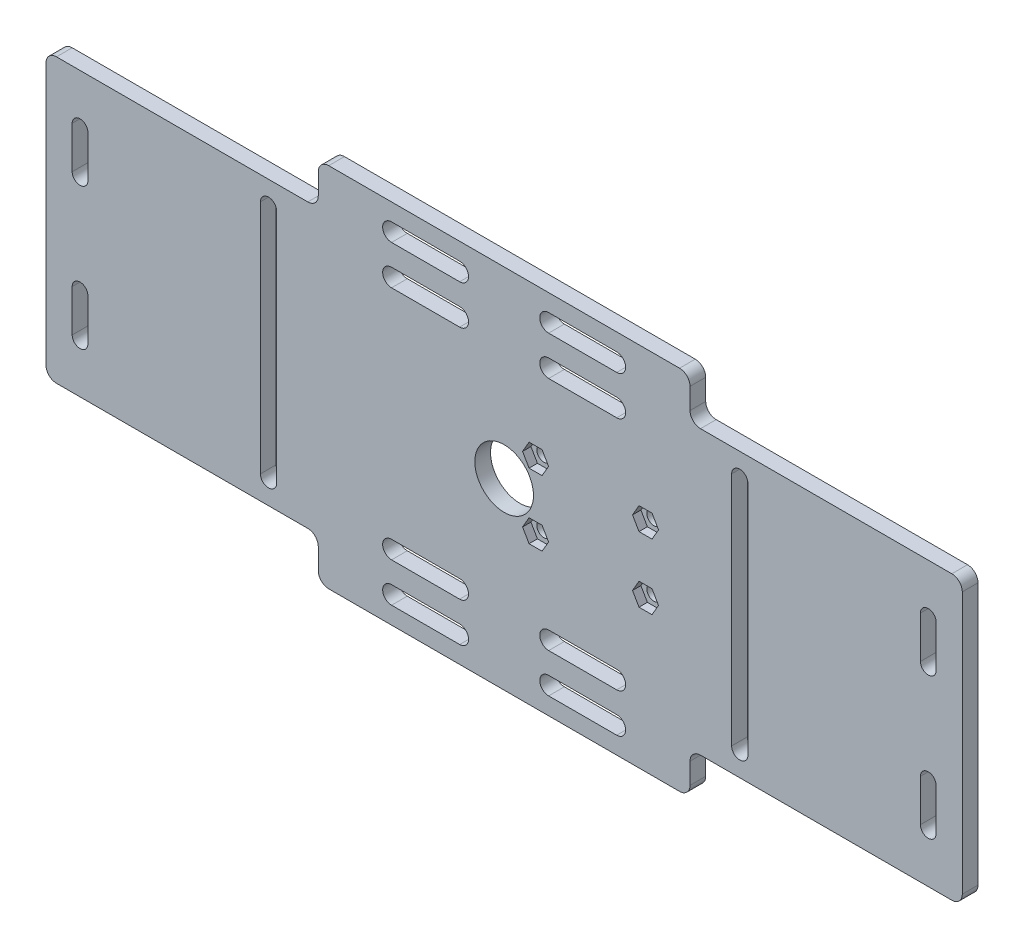
SolidWorks part; units mm, degrees
ref_plane "前基準面" through (0, 0, 0) normal (0, 0, 1) x (1, 0, 0)
ref_plane "上基準面" through (0, 0, 0) normal (0, 1, 0) x (1, 0, 0)
ref_plane "右基準面" through (0, 0, 0) normal (1, 0, 0) x (0, 0, -1)
sketch "草圖1" plane through (0, 0, 0) normal (0, 0, 1) x (1, 0, 0)
  line L0 (35.5, 33) -> (35.5, 29)
  line L1 (-33.5, 35) -> (33.5, 35)
  line L2 (-87.5, 25) -> (-87.5, -25)
  line L3 (-33.5, -35) -> (33.5, -35)
  line L4 (87.5, 25) -> (87.5, -25)
  line L5 (-87.5, 35) -> (87.5, -35) construction
  line L6 (-87.5, -35) -> (87.5, 35) construction
  line L7 (37.5, 27) -> (85.5, 27)
  line L8 (0, 71.4811) -> (0, -70.0061) construction
  line L9 (-113.0104, 0) -> (128.372, 0) construction
  line L10 (-37.5, 27) -> (-85.5, 27)
  line L11 (-35.5, 33) -> (-35.5, 29)
  line L12 (37.5, -27) -> (85.5, -27)
  line L13 (35.5, -33) -> (35.5, -29)
  line L14 (-35.5, -33) -> (-35.5, -29)
  line L15 (-37.5, -27) -> (-85.5, -27)
  arc A0 (35.5, 33) -> (33.5, 35) centre (33.5, 33) ccw
  arc A1 (37.5, 27) -> (35.5, 29) centre (37.5, 29) cw
  arc A2 (87.5, 25) -> (85.5, 27) centre (85.5, 25) ccw
  arc A3 (-87.5, 25) -> (-85.5, 27) centre (-85.5, 25) cw
  arc A4 (-37.5, 27) -> (-35.5, 29) centre (-37.5, 29) ccw
  arc A5 (-35.5, 33) -> (-33.5, 35) centre (-33.5, 33) cw
  arc A6 (87.5, -25) -> (85.5, -27) centre (85.5, -25) cw
  arc A7 (37.5, -27) -> (35.5, -29) centre (37.5, -29) ccw
  arc A8 (35.5, -33) -> (33.5, -35) centre (33.5, -33) cw
  arc A9 (-35.5, -33) -> (-33.5, -35) centre (-33.5, -33) ccw
  arc A10 (-37.5, -27) -> (-35.5, -29) centre (-37.5, -29) cw
  arc A11 (-87.5, -25) -> (-85.5, -27) centre (-85.5, -25) ccw
  point P0 (0, 0)
  point P13 (35.5, 27)
  point P29 (-35.5, 27)
  point P39 (35.5, -27)
  point P49 (-35.5, -27)
  dimension "D1" = 2
  dimension "D2" = 2
  dimension "D3" = 2
  dimension "D4" = 175
  dimension "D5" = 70
  dimension "D6" = 8
  dimension "D7" = 52
extrude "填料-伸長1" add sketch "草圖1" along normal blind 3
sketch "草圖2" plane through (0, 0, 3) normal (0, 0, 1) x (1, 0, 0)
  line L0 (-1000, 0) -> (49000, 0) construction
  line L1 (45, -986.1952) -> (45, 49013.8048) construction
  line L2 (-81, -962.7943) -> (-81, 49037.2057) construction
  line L3 (45, -22.5) -> (45, 22.5) construction
  line L4 (43.45, -22.5) -> (43.45, 22.5)
  line L5 (46.55, -22.5) -> (46.55, 22.5)
  line L6 (-45, -1000) -> (-45, 49000) construction
  line L7 (-45, -22.5) -> (-45, 22.5) construction
  line L8 (-46.55, -22.5) -> (-46.55, 22.5)
  line L9 (-43.45, -22.5) -> (-43.45, 22.5)
  line L10 (0, -1000) -> (0, 49000) construction
  line L11 (-1010.5287, 30) -> (48989.4713, 30) construction
  line L12 (-1007.193, -30) -> (48992.807, -30) construction
  line L13 (21.5, -30) -> (8.5, -30) construction
  line L16 (6, -996.0597) -> (6, 49003.9403) construction
  line L19 (81, -968.4295) -> (81, 49031.5705) construction
  line L20 (-81, -17.5) -> (-81, 17.5) construction
  line L21 (-82.5, -17.5) -> (-82.5, 17.5) construction
  line L22 (-79.5, -17.5) -> (-79.5, 17.5) construction
  line L23 (81, -17.5) -> (81, 17.5) construction
  line L24 (79.5, -17.5) -> (79.5, 17.5) construction
  line L25 (82.5, -17.5) -> (82.5, 17.5) construction
  line L26 (27, -997.4467) -> (27, 49002.5533) construction
  line L27 (-1014.4971, -6.25) -> (48985.5029, -6.25) construction
  line L28 (-1015.8254, 6.25) -> (48984.1746, 6.25) construction
  line L29 (-33.5, -35) -> (33.5, -35) construction
  line L30 (21.5, -31.7) -> (8.5, -31.7)
  line L33 (21.5, -28.3) -> (8.5, -28.3)
  line L34 (-21.5, -30) -> (-8.5, -30) construction
  line L35 (-21.5, -31.7) -> (-8.5, -31.7)
  line L36 (-21.5, -28.3) -> (-8.5, -28.3)
  line L37 (21.5, 30) -> (8.5, 30) construction
  line L38 (21.5, 31.7) -> (8.5, 31.7)
  line L39 (21.5, 28.3) -> (8.5, 28.3)
  line L40 (-21.5, 30) -> (-8.5, 30) construction
  line L41 (-21.5, 31.7) -> (-8.5, 31.7)
  line L42 (-21.5, 28.3) -> (-8.5, 28.3)
  line L43 (21.5, 22.5) -> (8.5, 22.5) construction
  line L44 (21.5, 24.2) -> (8.5, 24.2)
  line L45 (21.5, 20.8) -> (8.5, 20.8)
  line L46 (-21.5, 22.5) -> (-8.5, 22.5) construction
  line L47 (-21.5, 24.2) -> (-8.5, 24.2)
  line L48 (-21.5, 20.8) -> (-8.5, 20.8)
  line L49 (-21.5, -22.5) -> (-8.5, -22.5) construction
  line L50 (-21.5, -24.2) -> (-8.5, -24.2)
  line L51 (-21.5, -20.8) -> (-8.5, -20.8)
  line L52 (21.5, -22.5) -> (8.5, -22.5) construction
  line L53 (21.5, -24.2) -> (8.5, -24.2)
  line L54 (21.5, -20.8) -> (8.5, -20.8)
  line L55 (-81, -17.5) -> (-81, -9.5) construction
  line L56 (-82.5, -17.5) -> (-82.5, -9.5)
  line L57 (-79.5, -17.5) -> (-79.5, -9.5)
  line L58 (-81, 17.5) -> (-81, 9.5) construction
  line L59 (-82.5, 17.5) -> (-82.5, 9.5)
  line L60 (-79.5, 17.5) -> (-79.5, 9.5)
  line L61 (81, -17.5) -> (81, -9.5) construction
  line L62 (79.5, -17.5) -> (79.5, -9.5)
  line L63 (82.5, -17.5) -> (82.5, -9.5)
  line L64 (81, 17.5) -> (81, 9.5) construction
  line L65 (79.5, 17.5) -> (79.5, 9.5)
  line L66 (82.5, 17.5) -> (82.5, 9.5)
  arc A0 (43.45, -22.5) -> (46.55, -22.5) centre (45, -22.5) ccw
  arc A1 (46.55, 22.5) -> (43.45, 22.5) centre (45, 22.5) ccw
  arc A2 (-46.55, -22.5) -> (-43.45, -22.5) centre (-45, -22.5) ccw
  arc A3 (-43.45, 22.5) -> (-46.55, 22.5) centre (-45, 22.5) ccw
  arc A12 (-82.5, -17.5) -> (-79.5, -17.5) centre (-81, -17.5) ccw construction
  arc A13 (-79.5, 17.5) -> (-82.5, 17.5) centre (-81, 17.5) ccw construction
  arc A14 (79.5, -17.5) -> (82.5, -17.5) centre (81, -17.5) ccw construction
  arc A15 (82.5, 17.5) -> (79.5, 17.5) centre (81, 17.5) ccw construction
  circle A16 centre (0, 0) radius 5.6
  circle A17 centre (27, 6.25) radius 1.35
  circle A18 centre (6, 6.25) radius 1.35
  circle A19 centre (6, -6.25) radius 1.35
  circle A20 centre (27, -6.25) radius 1.35
  arc A23 (21.5, -31.7) -> (21.5, -28.3) centre (21.5, -30) ccw
  arc A24 (8.5, -28.3) -> (8.5, -31.7) centre (8.5, -30) ccw
  arc A25 (-21.5, -31.7) -> (-21.5, -28.3) centre (-21.5, -30) cw
  arc A26 (-8.5, -28.3) -> (-8.5, -31.7) centre (-8.5, -30) cw
  arc A27 (21.5, 31.7) -> (21.5, 28.3) centre (21.5, 30) cw
  arc A28 (8.5, 28.3) -> (8.5, 31.7) centre (8.5, 30) cw
  arc A29 (-21.5, 31.7) -> (-21.5, 28.3) centre (-21.5, 30) ccw
  arc A30 (-8.5, 28.3) -> (-8.5, 31.7) centre (-8.5, 30) ccw
  arc A31 (21.5, 24.2) -> (21.5, 20.8) centre (21.5, 22.5) cw
  arc A32 (8.5, 20.8) -> (8.5, 24.2) centre (8.5, 22.5) cw
  arc A33 (-21.5, 24.2) -> (-21.5, 20.8) centre (-21.5, 22.5) ccw
  arc A34 (-8.5, 20.8) -> (-8.5, 24.2) centre (-8.5, 22.5) ccw
  arc A35 (-21.5, -24.2) -> (-21.5, -20.8) centre (-21.5, -22.5) cw
  arc A36 (-8.5, -20.8) -> (-8.5, -24.2) centre (-8.5, -22.5) cw
  arc A37 (21.5, -24.2) -> (21.5, -20.8) centre (21.5, -22.5) ccw
  arc A38 (8.5, -20.8) -> (8.5, -24.2) centre (8.5, -22.5) ccw
  arc A43 (-82.5, -17.5) -> (-79.5, -17.5) centre (-81, -17.5) ccw
  arc A44 (-79.5, -9.5) -> (-82.5, -9.5) centre (-81, -9.5) ccw
  arc A45 (-82.5, 17.5) -> (-79.5, 17.5) centre (-81, 17.5) cw
  arc A46 (-79.5, 9.5) -> (-82.5, 9.5) centre (-81, 9.5) cw
  arc A47 (79.5, -17.5) -> (82.5, -17.5) centre (81, -17.5) ccw
  arc A48 (82.5, -9.5) -> (79.5, -9.5) centre (81, -9.5) ccw
  arc A49 (79.5, 17.5) -> (82.5, 17.5) centre (81, 17.5) cw
  arc A50 (82.5, 9.5) -> (79.5, 9.5) centre (81, 9.5) cw
  point P9 (45, 0)
  point P16 (-45, 0)
  point P31 (15, -30)
  point P47 (-81, 0)
  point P54 (81, 0)
  point P72 (-15, -30)
  point P81 (15, 30)
  point P88 (-15, 30)
  point P97 (15, 22.5)
  point P102 (-15, 22.5)
  point P110 (-15, -22.5)
  point P116 (15, -22.5)
  point P127 (81, -13.5)
  point P129 (-81, -13.5)
  point P134 (-81, 13.5)
  point P144 (81, 13.5)
  dimension "D10" = 1.7
  dimension "D20" = 11.2
  dimension "D21" = 2.7
  dimension "D27" = 7.5
  dimension "D2" = 45
  dimension "D3" = 3.1
  dimension "D4" = 90
  dimension "D5" = 45
  dimension "D6" = 3.1
  dimension "D7" = 45
  dimension "D8" = 60
  dimension "D9" = 30
  dimension "D11" = 13
  dimension "D12" = 12.5
  dimension "D13" = 21
  dimension "D14" = 162
  dimension "D15" = 81
  dimension "D16" = 3
  dimension "D17" = 35
  dimension "D18" = 35
  dimension "D19" = 3
  dimension "D22" = 28.75
  dimension "D23" = 6
  dimension "D24" = 8.5
  dimension "D25" = 2
  dimension "D28" = 7.5
  dimension "D29" = 8
  dimension "D30" = 8
  dimension "D26" = 2
extrude "除料-伸長1" cut sketch "草圖2" against normal through all
sketch "草圖3" plane through (0, 0, 3) normal (0, 0, 1) x (1, 0, 0)
  line L0 (29.4826, -6.25) -> (28.2413, -4.1)
  line L1 (8.4826, -6.25) -> (7.2413, -4.1)
  line L2 (7.2413, -4.1) -> (4.7587, -4.1)
  line L3 (4.7587, -4.1) -> (3.5174, -6.25)
  line L4 (3.5174, -6.25) -> (4.7587, -8.4)
  line L5 (4.7587, -8.4) -> (7.2413, -8.4)
  line L6 (7.2413, -8.4) -> (8.4826, -6.25)
  line L7 (28.2413, -4.1) -> (25.7587, -4.1)
  line L8 (25.7587, -4.1) -> (24.5174, -6.25)
  line L9 (24.5174, -6.25) -> (25.7587, -8.4)
  line L10 (25.7587, -8.4) -> (28.2413, -8.4)
  line L11 (28.2413, -8.4) -> (29.4826, -6.25)
  line L12 (29.4826, 6.25) -> (28.2413, 8.4)
  line L13 (28.2413, 8.4) -> (25.7587, 8.4)
  line L14 (25.7587, 8.4) -> (24.5174, 6.25)
  line L15 (24.5174, 6.25) -> (25.7587, 4.1)
  line L16 (25.7587, 4.1) -> (28.2413, 4.1)
  line L17 (28.2413, 4.1) -> (29.4826, 6.25)
  line L18 (8.4826, 6.25) -> (7.2413, 8.4)
  line L19 (7.2413, 8.4) -> (4.7587, 8.4)
  line L20 (4.7587, 8.4) -> (3.5174, 6.25)
  line L21 (3.5174, 6.25) -> (4.7587, 4.1)
  line L22 (4.7587, 4.1) -> (7.2413, 4.1)
  line L23 (7.2413, 4.1) -> (8.4826, 6.25)
  circle A0 centre (6, -6.25) radius 2.15 construction
  circle A3 centre (27, -6.25) radius 2.15 construction
  circle A4 centre (27, 6.25) radius 2.15 construction
  circle A5 centre (6, 6.25) radius 2.15 construction
  dimension "D1" = 4.3
  dimension "D2" = 2
  dimension "D3" = 2
extrude "除料-伸長2" cut sketch "草圖3" against normal blind 1.6
sketch "草圖4" plane through (0, 0, 0) normal (0, 0, -1) x (-1, 0, 0)
  circle A0 centre (-27, 6.25) radius 1.35
  circle A1 centre (-27, -6.25) radius 1.25
  circle A2 centre (-6, 6.25) radius 1.25
  circle A3 centre (-6, -6.25) radius 1.25
  circle A4 centre (-27, 6.25) radius 2.1
  circle A5 centre (-27, -6.25) radius 2
  circle A6 centre (-6, 6.25) radius 2
  circle A7 centre (-6, -6.25) radius 2
  circle A8 centre (-27, 6.25) radius 1.35 construction
  dimension "D1" = 0.75
extrude "填料-伸長2" add sketch "草圖4" along normal blind 2
chamfer "導角1" distance 0.5 angle 30 4 edges at (25.65, 6.25, -2) (4.75, 6.25, -2) (4.75, -6.25, -2) (25.75, -6.25, -2)
fillet "圓角2" radius 0.5 4 edges at (29.1, 6.25, 0) (8, 6.25, 0) (8, -6.25, 0) (29, -6.25, 0)
